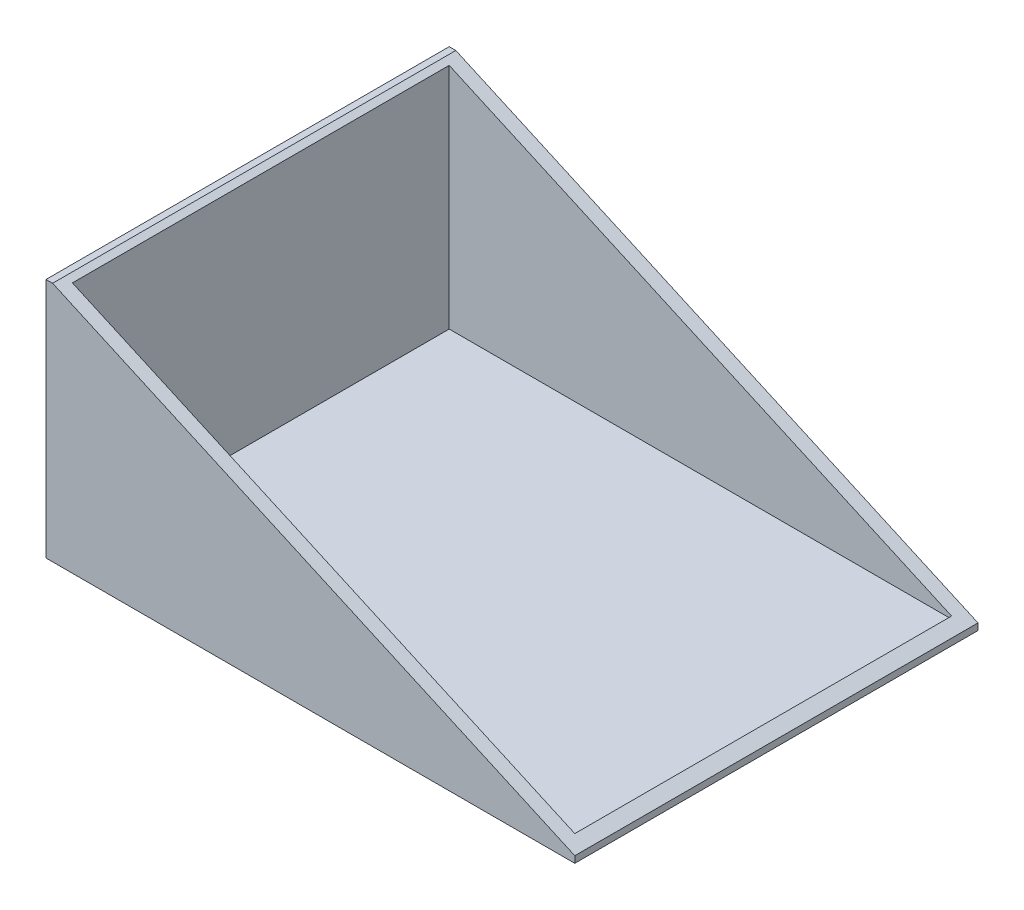
SolidWorks part; units mm, degrees
ref_plane "前视基准面" through (0, 0, 0) normal (0, 0, 1) x (1, 0, 0)
ref_plane "上视基准面" through (0, 0, 0) normal (0, 1, 0) x (1, 0, 0)
ref_plane "右视基准面" through (0, 0, 0) normal (1, 0, 0) x (0, 0, -1)
sketch "草图1" plane through (0, 0, 0) normal (0, 1, 0) x (1, 0, 0)
  line L1 (0, 0) -> (80, 0)
  line L2 (0, 0) -> (0, 61)
  line L3 (0, 61) -> (80, 61)
  line L4 (80, 0) -> (80, 61)
  dimension "D1" = 80
  dimension "D2" = 61
extrude "凸台-拉伸1" add sketch "草图1" along normal blind 1.5
sketch "草图5" plane through (0, 1.5, 0) normal (0, 1, 0) x (1, 0, 0)
  line L0 (78, 59) -> (78, 2)
  line L1 (0, 61) -> (80, 61)
  line L2 (0, 61) -> (0, 0)
  line L3 (0, 0) -> (80, 0)
  line L4 (80, 61) -> (80, 0)
  line L5 (2, 2) -> (78, 2)
  line L6 (2, 59) -> (2, 2)
  line L7 (2, 59) -> (78, 59)
  dimension "D1" = 2
extrude "凸台-拉伸3" add sketch "草图5" along normal blind 35
sketch "草图6" plane through (0, 0, 0) normal (0, 0, 1) x (1, 0, 0)
  line L0 (1, 36.5) -> (80, 36.5)
  line L1 (0, 36.5) -> (80, 36.5) construction
  line L2 (80, 36.5) -> (80, 0) construction
  line L3 (80, 36.5) -> (80, 1)
  line L4 (80, 1) -> (1, 36.5)
  line L5 (0, 36.5) -> (0, 0) construction
  line L6 (0, 0) -> (80, 0) construction
  dimension "D1" = 1
  dimension "D2" = 1
extrude "切除-拉伸2" cut sketch "草图6" against normal through all
